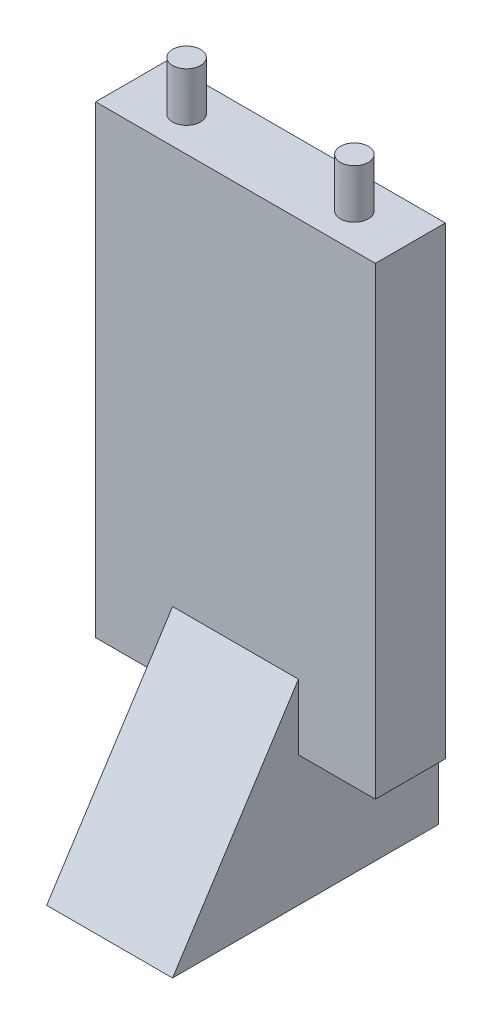
SolidWorks part; units mm, degrees
ref_plane "Front Plane" through (0, 0, 0) normal (0, 0, 1) x (1, 0, 0)
ref_plane "Top Plane" through (0, 0, 0) normal (0, 1, 0) x (1, 0, 0)
ref_plane "Right Plane" through (0, 0, 0) normal (1, 0, 0) x (0, 0, -1)
sketch "Sketch1" plane through (0, 0, 0) normal (0, 1, 0) x (1, 0, 0)
  line L1 (0, -10.671) -> (-21.342, -10.671) construction
  line L7 (-21.342, -10.671) -> (80.258, -10.671)
  line L8 (-21.342, -10.671) -> (-21.342, 14.729)
  line L9 (-21.342, 14.729) -> (80.258, 14.729)
  line L10 (80.258, -10.671) -> (80.258, 14.729)
extrude "Boss-Extrude1" add sketch "Sketch1" along normal blind 215.9 contours L9 L10 L7 L8
sketch "Sketch2" plane through (0, 215.9, 0) normal (0, 1, 0) x (1, 0, 0)
  line L0 (29.458, 14.729) -> (29.458, -10.671) construction
  line L1 (-21.342, 14.729) -> (80.258, 14.729) construction
  line L2 (-21.342, -10.671) -> (80.258, -10.671) construction
  line L3 (29.458, 2.029) -> (15.488, 2.029) construction
  line L4 (29.458, 2.029) -> (-1.022, 2.029) construction
  line L5 (29.458, 2.029) -> (59.938, 2.029) construction
  circle A1 centre (-1.022, 2.029) radius 5.08
  circle A2 centre (59.938, 2.029) radius 5.08
  dimension "D1" = 10.16
  dimension "D2" = 10.16
extrude "Boss-Extrude2" add sketch "Sketch2" along normal blind 17.78
sketch "Sketch3" plane through (0, 0, 10.671) normal (0, 0, 1) x (1, 0, 0)
  line L1 (-21.342, 0) -> (6.598, 0)
  line L2 (-21.342, 0) -> (-21.342, 47.3461)
  line L3 (-21.342, 47.3461) -> (6.598, 47.3461)
  line L4 (6.598, 0) -> (6.598, 47.3461)
  line L5 (80.258, 0) -> (52.318, 0)
  line L6 (80.258, 0) -> (80.258, 47.3461)
  line L7 (80.258, 47.3461) -> (52.318, 47.3461)
  line L8 (52.318, 0) -> (52.318, 47.3461)
extrude "Cut-Extrude1" cut sketch "Sketch3" against normal blind 27.686
sketch "Sketch9" plane through (0, 0, 10.671) normal (0, 0, 1) x (1, 0, 0)
  line L1 (6.598, 0) -> (52.318, 0)
  line L2 (6.598, 0) -> (6.598, 71.12)
  line L3 (6.598, 71.12) -> (52.318, 71.12)
  line L4 (52.318, 0) -> (52.318, 71.12)
extrude "Boss-Extrude5" add sketch "Sketch9" along normal blind 45.72
sketch "Sketch10" plane through (52.318, 0, 0) normal (1, 0, 0) x (0, 0, -1)
  line L0 (-56.391, 71.12) -> (-10.671, 71.12)
  line L1 (-10.671, 71.12) -> (-56.391, 0)
  line L2 (-56.391, 0) -> (-56.391, 71.12)
extrude "Cut-Extrude4" cut sketch "Sketch10" against normal blind 45.72
sketch "Sketch11" plane through (0, 0, -14.729) normal (0, 0, -1) x (-1, 0, 0)
  line L0 (-52.318, 47.3461) -> (-52.318, 70.9794)
  line L1 (-6.598, 47.3461) -> (-6.598, 70.9794)
  line L2 (-6.598, 70.9794) -> (-52.318, 70.9794)
  line L3 (-52.318, 47.3461) -> (-52.318, 0)
  line L4 (-52.318, 0) -> (-6.598, 0)
  line L5 (-6.598, 0) -> (-6.598, 47.3461)
extrude "Boss-Extrude6" add sketch "Sketch11" along normal blind 25.4
